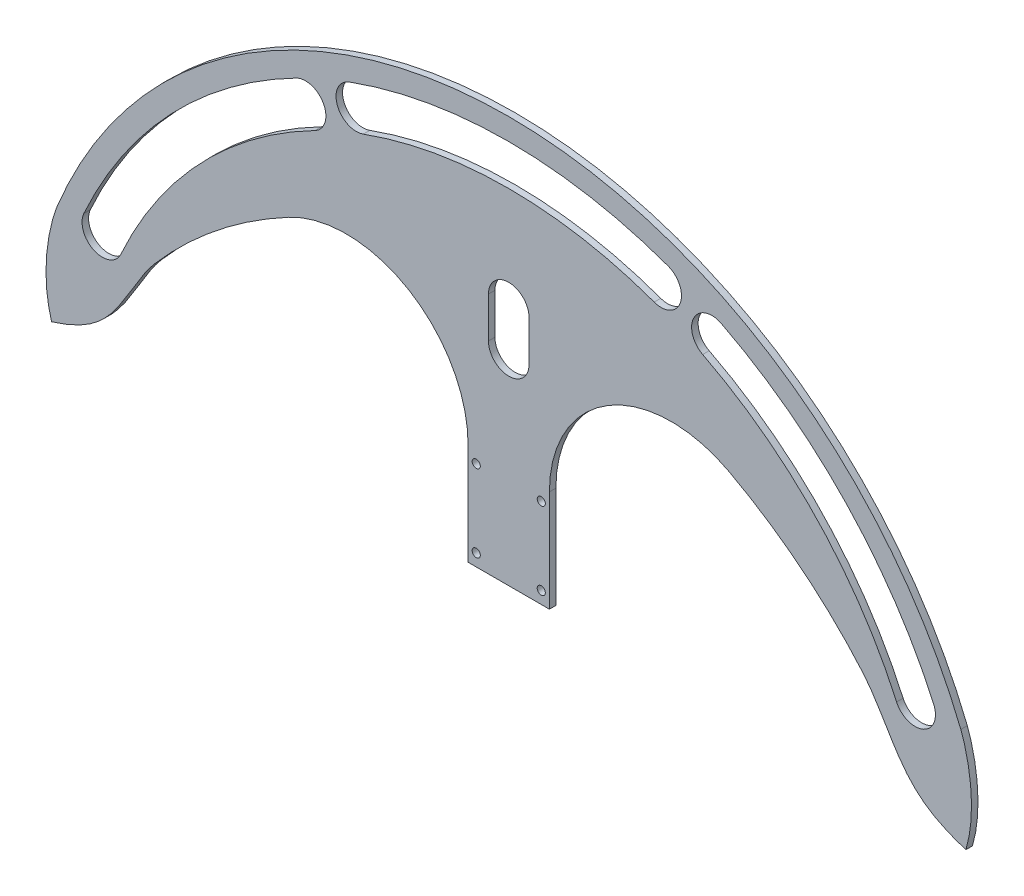
SolidWorks part; units mm, degrees
ref_plane "前视基准面" through (0, 0, 0) normal (0, 0, 1) x (1, 0, 0)
ref_plane "上视基准面" through (0, 0, 0) normal (0, 1, 0) x (1, 0, 0)
ref_plane "右视基准面" through (0, 0, 0) normal (1, 0, 0) x (0, 0, -1)
sketch "草图1" plane through (0, 0, 0) normal (0, 0, 1) x (1, 0, 0)
  line L0 (0, -43.7947) -> (0, 156.157) construction
  line L1 (12.5, 164.972) -> (12.5, 364.9237) construction
  line L6 (-10, 0) -> (10, 0)
  line L7 (-10, 0) -> (-10, 25)
  line L8 (0, 100) -> (0, 70) construction
  line L9 (2.0803, 85) -> (-53.4271, 85) construction
  line L10 (-169.4329, 25) -> (156.9904, 25) construction
  line L12 (10, 0) -> (10, 25)
  line L13 (25, 177.5031) -> (25, 377.4548) construction
  line L14 (37.5, 167.3589) -> (37.5, 367.3105) construction
  line L15 (50, 165.9665) -> (50, 365.9182) construction
  line L16 (62.5, 163.1818) -> (62.5, 363.1335) construction
  line L17 (75, 157.6296) -> (75, 357.5813) construction
  line L18 (87.5, 154.1198) -> (87.5, 354.0715) construction
  line L19 (100, 151.7799) -> (100, 351.7316) construction
  line L20 (-100, 151.7799) -> (-100, 351.7316) construction
  line L21 (-87.5, 154.1198) -> (-87.5, 354.0715) construction
  line L22 (-75, 157.6296) -> (-75, 357.5813) construction
  line L23 (-62.5, 163.1818) -> (-62.5, 363.1335) construction
  line L24 (-50, 165.9665) -> (-50, 365.9182) construction
  line L25 (-37.5, 167.3589) -> (-37.5, 367.3105) construction
  line L26 (-25, 177.5031) -> (-25, 377.4548) construction
  line L27 (-12.5, 164.972) -> (-12.5, 364.9237) construction
  line L28 (-112.5, 0) -> (112.5, 0) construction
  line L29 (0, 59.6586) -> (0, 49.6586) construction
  line L30 (5, 59.6586) -> (5, 49.6586)
  line L31 (-5, 59.6586) -> (-5, 49.6586)
  arc A1 (87.178, 25) -> (54.1176, 51.4706) centre (0, -50) ccw
  arc A2 (-54.1176, 51.4706) -> (-87.178, 25) centre (0, -50) ccw
  arc A3 (10, 25) -> (54.1176, 51.4706) centre (40, 25) cw
  arc A4 (-10, 25) -> (-54.1176, 51.4706) centre (-40, 25) ccw
  circle A5 centre (0, -50) radius 115 construction
  arc A6 (-100, 25) -> (-50, 77.5961) centre (0, -20) cw construction
  arc A11 (-111.243, 25) -> (111.243, 25) centre (0, -20) cw
  arc A12 (-52.2798, 82.0461) -> (-104.5596, 27.0518) centre (0, -20) ccw
  arc A13 (-47.7202, 73.1461) -> (-95.4404, 22.9482) centre (0, -20) ccw
  arc A14 (-47.7202, 73.1461) -> (-52.2798, 82.0461) centre (-50, 77.5961) ccw
  arc A15 (-104.5596, 27.0518) -> (-95.4404, 22.9482) centre (-100, 25) ccw
  circle A16 centre (0, -20) radius 109.6586 construction
  arc A17 (100, 25) -> (50, 77.5961) centre (0, -20) ccw construction
  arc A18 (52.2798, 82.0461) -> (104.5596, 27.0518) centre (0, -20) cw
  arc A19 (47.7202, 73.1461) -> (95.4404, 22.9482) centre (0, -20) cw
  arc A20 (47.7202, 73.1461) -> (52.2798, 82.0461) centre (50, 77.5961) cw
  arc A21 (104.5596, 27.0518) -> (95.4404, 22.9482) centre (100, 25) cw
  arc A22 (-37.5, 83.0473) -> (37.5, 83.0473) centre (0, -20) cw construction
  arc A23 (39.2099, 87.7459) -> (-39.2099, 87.7459) centre (0, -20) ccw
  arc A24 (35.7901, 78.3488) -> (-35.7901, 78.3488) centre (0, -20) ccw
  arc A25 (35.7901, 78.3488) -> (39.2099, 87.7459) centre (37.5, 83.0473) ccw
  arc A26 (-39.2099, 87.7459) -> (-35.7901, 78.3488) centre (-37.5, 83.0473) ccw
  arc A27 (5, 59.6586) -> (-5, 59.6586) centre (0, 59.6586) ccw
  arc A28 (-5, 49.6586) -> (5, 49.6586) centre (0, 49.6586) ccw
  spline S0 degree 3 poles (-87.178, 25) (-90.305, 21.3652) (-96.2479, 9.4434) (-103.4503, 2.7758) (-112.5, 0) knots 0 0 0 0 0.445001 1 1 1 1
  spline S1 degree 3 poles (87.178, 25) (90.305, 21.3652) (96.2479, 9.4434) (103.4503, 2.7758) (112.5, 0) knots 0 0 0 0 0.445001 1 1 1 1
  spline S2 degree 3 poles (-111.243, 25) (-112.5288, 21.8214) (-115.6682, 10.743) (-112.5, 0) knots 0 0 0 0 1 1 1 1
  spline S3 degree 3 poles (111.243, 25) (112.5288, 21.8214) (115.6682, 10.743) (112.5, 0) knots 0 0 0 0 1 1 1 1
  point P59 (-10, 64.5644)
  point P64 (-79.477, 55.554)
  point P76 (79.477, 55.554)
  point P84 (0, 89.6586)
  point P91 (0, 54.6586)
  dimension "D1" = 225
  dimension "D2" = 15
  dimension "D12" = 30
  dimension "D16" = 230
  dimension "D17" = 120
  dimension "D18" = 10
  dimension "D19" = 10
  dimension "D3" = 12.5
  dimension "D4" = 60
  dimension "D5" = 12.5
  dimension "D6" = 12.5
  dimension "D7" = 12.5
  dimension "D8" = 12.5
  dimension "D9" = 12.5
  dimension "D10" = 12.5
  dimension "D11" = 12.5
  dimension "D13" = 20
  dimension "D14" = 50
  dimension "D15" = 100
  dimension "D20" = 30
  dimension "D21" = 10
  dimension "D22" = 10
  dimension "D23" = 25
extrude "凸台-拉伸2" add sketch "草图1" along normal blind 1.6
sketch "草图2" plane through (0, 0, 1.6) normal (0, 0, 1) x (1, 0, 0)
  line L0 (0, 0) -> (0, 114.3816) construction
  line L2 (-10, 25) -> (-10, 0) construction
  line L3 (-10, 0) -> (10, 0) construction
  line L4 (10, 0) -> (10, 25) construction
  circle A0 centre (-8, 3) radius 1
  circle A1 centre (8, 3) radius 1
  circle A2 centre (-8, 22) radius 1
  circle A3 centre (8, 22) radius 1
  dimension "D2" = 3
  dimension "D3" = 2
  dimension "D4" = 19
  dimension "D5" = 2
  dimension "D1" = 2
  dimension "D6" = 2
extrude "切除-拉伸1" cut sketch "草图2" against normal through all
